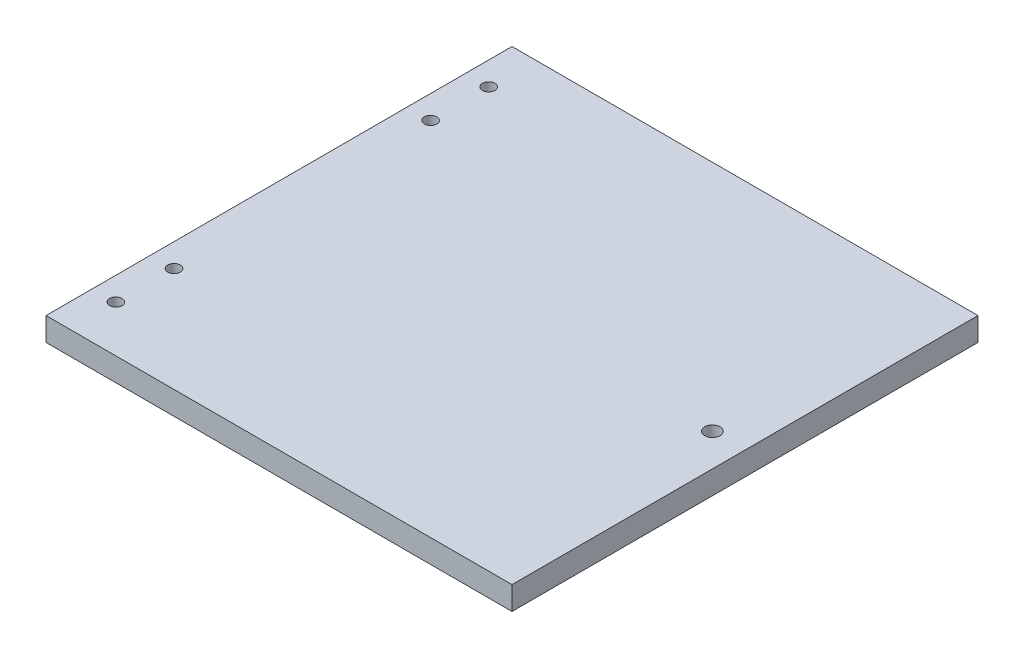
SolidWorks part; units mm, degrees
material "Acrylic (Medium-high impact)"
ref_plane "Front Plane" through (0, 0, 0) normal (0, 0, 1) x (1, 0, 0)
ref_plane "Top Plane" through (0, 0, 0) normal (0, 1, 0) x (1, 0, 0)
ref_plane "Right Plane" through (0, 0, 0) normal (1, 0, 0) x (0, 0, -1)
sketch "Sketch1" plane through (0, 0, 0) normal (0, 1, 0) x (1, 0, 0)
  line L1 (-93.29, 51.9943) -> (33.71, 51.9943)
  line L2 (-93.29, 51.9943) -> (-93.29, -75.0057)
  line L3 (-93.29, -75.0057) -> (33.71, -75.0057)
  line L4 (33.71, 51.9943) -> (33.71, -75.0057)
  circle A0 centre (24.82, -11.5057) radius 2.1018
  circle A1 centre (-86.94, 23.4574) radius 1.7018
  circle A2 centre (-86.94, 39.2943) radius 1.7018
  circle A3 centre (-86.94, -62.3057) radius 1.7018
  circle A4 centre (-86.94, -46.4688) radius 1.7018
  point P10 (-79.7374, 36.3899)
  point P11 (-79.7374, 22.0664)
  point P16 (-79.7374, -55.0475)
  point P17 (-79.7374, -67.539)
  dimension "D3" = 4.2037
  dimension "D6" = 3.4036
  dimension "D7" = 3.4036
  dimension "D8" = 3.4036
  dimension "D9" = 3.4036
  dimension "D1" = 127
  dimension "D2" = 127
  dimension "D4" = 63.5
  dimension "D5" = 8.89
  dimension "D10" = 15.8369
  dimension "D11" = 15.8369
  dimension "D12" = 6.35
  dimension "D13" = 6.35
  dimension "D14" = 12.7
  dimension "D15" = 12.7
extrude "Boss-Extrude1" add sketch "Sketch1" along normal blind 6.35
